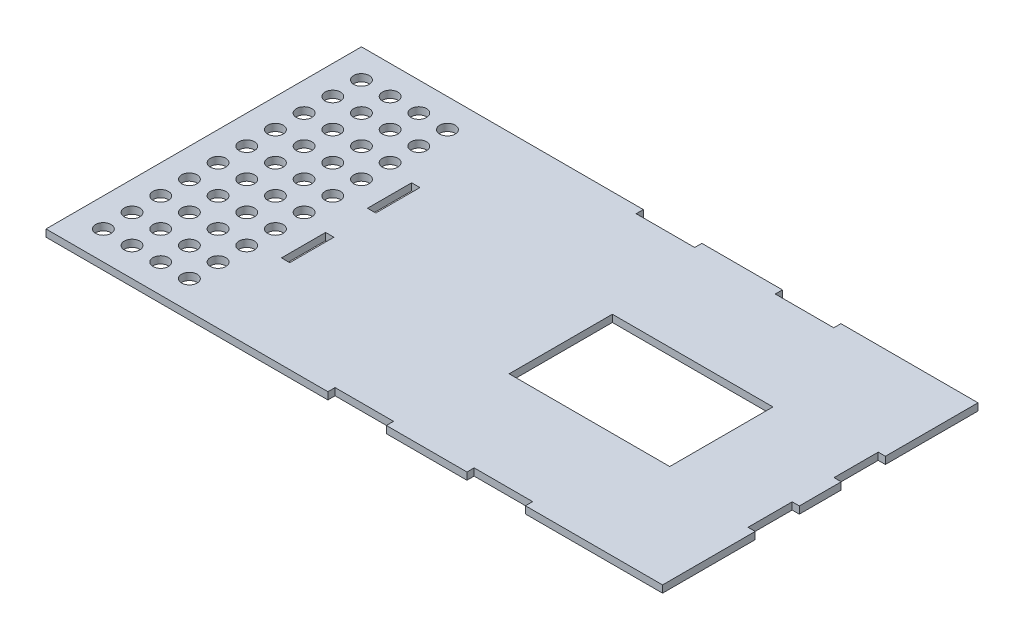
SolidWorks part; units mm, degrees
ref_plane "Front Plane" through (0, 0, 0) normal (0, 0, 1) x (1, 0, 0)
ref_plane "Top Plane" through (0, 0, 0) normal (0, 1, 0) x (1, 0, 0)
ref_plane "Right Plane" through (0, 0, 0) normal (1, 0, 0) x (0, 0, -1)
sketch "Sketch1" plane through (0, 0, 0) normal (0, 1, 0) x (1, 0, 0)
  line L1 (-101.6, -66.675) -> (101.6, -66.675)
  line L2 (-101.6, -66.675) -> (-101.6, 66.675)
  line L3 (-101.6, 66.675) -> (101.6, 66.675)
  line L4 (101.6, -66.675) -> (101.6, 66.675)
  line L5 (-101.6, -66.675) -> (101.6, 66.675) construction
  line L6 (-101.6, 66.675) -> (101.6, -66.675) construction
  point P0 (0, 0)
  dimension "D1" = 203.2
  dimension "D2" = 133.35
extrude "Boss-Extrude1" add sketch "Sketch1" along normal blind 3.175
sketch "Sketch3" plane through (0, 3.175, 0) normal (0, 1, 0) x (1, 0, 0)
  line L0 (101.6, 66.675) -> (-101.6, 66.675) construction
  line L1 (-79.121, 66.675) -> (-43.434, 66.675)
  line L2 (-79.121, 66.675) -> (-79.121, 69.85)
  line L3 (-79.121, 69.85) -> (-43.434, 69.85)
  line L4 (-43.434, 66.675) -> (-43.434, 69.85)
  line L5 (-101.6, 66.675) -> (-101.6, -66.675) construction
  line L6 (-17.526, 66.675) -> (18.161, 66.675)
  line L7 (18.161, 66.675) -> (18.161, 69.85)
  line L8 (-17.526, 69.85) -> (18.161, 69.85)
  line L9 (-17.526, 66.675) -> (-17.526, 69.85)
  line L10 (44.069, 66.675) -> (79.756, 66.675)
  line L11 (79.756, 66.675) -> (79.756, 69.85)
  line L12 (44.069, 69.85) -> (79.756, 69.85)
  line L13 (44.069, 66.675) -> (44.069, 69.85)
  line L14 (0, 0) -> (101.6, 0) construction
  line L15 (101.6, -66.675) -> (101.6, 66.675) construction
  line L16 (44.069, -66.675) -> (44.069, -69.85)
  line L17 (44.069, -69.85) -> (79.756, -69.85)
  line L18 (79.756, -66.675) -> (79.756, -69.85)
  line L19 (44.069, -66.675) -> (79.756, -66.675)
  line L20 (-17.526, -66.675) -> (-17.526, -69.85)
  line L21 (-17.526, -69.85) -> (18.161, -69.85)
  line L22 (18.161, -66.675) -> (18.161, -69.85)
  line L23 (-17.526, -66.675) -> (18.161, -66.675)
  line L24 (-43.434, -66.675) -> (-43.434, -69.85)
  line L25 (-79.121, -69.85) -> (-43.434, -69.85)
  line L26 (-79.121, -66.675) -> (-79.121, -69.85)
  line L27 (-79.121, -66.675) -> (-43.434, -66.675)
  point P6 (-61.2775, 66.675)
  dimension "D1" = 3.175
  dimension "D2" = 40.3225
  dimension "D3" = 22.479
  dimension "D4" = 35.687
  dimension "D5" = 3
extrude "Boss-Extrude2" add sketch "Sketch3" against normal blind 3.175
sketch "Sketch4" plane through (0, 3.175, 0) normal (0, 1, 0) x (1, 0, 0)
  line L0 (-101.6, 66.675) -> (-101.6, -66.675) construction
  line L1 (-101.6, 47.371) -> (-104.775, 47.371)
  line L2 (-101.6, 47.371) -> (-101.6, 28.829)
  line L3 (-101.6, 28.829) -> (-104.775, 28.829)
  line L4 (-104.775, 47.371) -> (-104.775, 28.829)
  line L5 (-104.775, 9.271) -> (-104.775, -9.271)
  line L6 (-79.121, 66.675) -> (-101.6, 66.675) construction
  line L7 (-101.6, -9.271) -> (-104.775, -9.271)
  line L8 (-101.6, 9.271) -> (-101.6, -9.271)
  line L9 (-101.6, 9.271) -> (-104.775, 9.271)
  line L10 (-104.775, -28.829) -> (-104.775, -47.371)
  line L11 (-101.6, -47.371) -> (-104.775, -47.371)
  line L12 (-101.6, -28.829) -> (-101.6, -47.371)
  line L13 (-101.6, -28.829) -> (-104.775, -28.829)
  line L14 (0, 0) -> (0, 30.8846) construction
  line L15 (101.6, -28.829) -> (104.775, -28.829)
  line L16 (101.6, -28.829) -> (101.6, -47.371)
  line L17 (101.6, -47.371) -> (104.775, -47.371)
  line L18 (104.775, -28.829) -> (104.775, -47.371)
  line L19 (101.6, 9.271) -> (104.775, 9.271)
  line L20 (101.6, 9.271) -> (101.6, -9.271)
  line L21 (101.6, -9.271) -> (104.775, -9.271)
  line L22 (104.775, 9.271) -> (104.775, -9.271)
  line L23 (104.775, 47.371) -> (104.775, 28.829)
  line L24 (101.6, 28.829) -> (104.775, 28.829)
  line L25 (101.6, 47.371) -> (101.6, 28.829)
  line L26 (101.6, 47.371) -> (104.775, 47.371)
  point P9 (-101.6, 38.1)
  point P10 (-103.1875, 47.371)
  dimension "D1" = 3.175
  dimension "D2" = 28.575
  dimension "D3" = 18.542
  dimension "D4" = 19.304
  dimension "D6" = 38.1
  dimension "D5" = 3
extrude "Boss-Extrude3" add sketch "Sketch4" against normal blind 3.175
sketch "Sketch5" plane through (0, 3.175, 0) normal (0, 1, 0) x (1, 0, 0)
  line L0 (-104.775, -28.829) -> (-104.775, -47.371) construction
  line L1 (-104.775, 69.85) -> (-168.275, 69.85)
  line L2 (-104.775, 69.85) -> (-104.775, -69.85)
  line L3 (-104.775, -69.85) -> (-168.275, -69.85)
  line L4 (-168.275, 69.85) -> (-168.275, -69.85)
  line L5 (-79.121, -69.85) -> (-43.434, -69.85) construction
  line L6 (-43.434, 69.85) -> (-79.121, 69.85) construction
  circle A0 centre (-117.475, 57.15) radius 3.429
  circle A1 centre (-130.175, 57.15) radius 3.429
  circle A2 centre (-142.875, 57.15) radius 3.429
  circle A3 centre (-155.575, 57.15) radius 3.429
  circle A4 centre (-130.175, 44.45) radius 3.429
  circle A5 centre (-142.875, 44.45) radius 3.429
  circle A6 centre (-155.575, 44.45) radius 3.429
  circle A7 centre (-130.175, 31.75) radius 3.429
  circle A8 centre (-142.875, 31.75) radius 3.429
  circle A9 centre (-155.575, 31.75) radius 3.429
  circle A10 centre (-130.175, 19.05) radius 3.429
  circle A11 centre (-142.875, 19.05) radius 3.429
  circle A12 centre (-155.575, 19.05) radius 3.429
  circle A13 centre (-130.175, 6.35) radius 3.429
  circle A14 centre (-142.875, 6.35) radius 3.429
  circle A15 centre (-155.575, 6.35) radius 3.429
  circle A16 centre (-130.175, -6.35) radius 3.429
  circle A17 centre (-142.875, -6.35) radius 3.429
  circle A18 centre (-155.575, -6.35) radius 3.429
  circle A19 centre (-130.175, -19.05) radius 3.429
  circle A20 centre (-142.875, -19.05) radius 3.429
  circle A21 centre (-155.575, -19.05) radius 3.429
  circle A22 centre (-130.175, -31.75) radius 3.429
  circle A23 centre (-142.875, -31.75) radius 3.429
  circle A24 centre (-155.575, -31.75) radius 3.429
  circle A25 centre (-130.175, -44.45) radius 3.429
  circle A26 centre (-142.875, -44.45) radius 3.429
  circle A27 centre (-155.575, -44.45) radius 3.429
  circle A28 centre (-130.175, -57.15) radius 3.429
  circle A29 centre (-142.875, -57.15) radius 3.429
  circle A30 centre (-155.575, -57.15) radius 3.429
  circle A31 centre (-117.475, 44.45) radius 3.429
  circle A32 centre (-117.475, 31.75) radius 3.429
  circle A33 centre (-117.475, 19.05) radius 3.429
  circle A34 centre (-117.475, 6.35) radius 3.429
  circle A35 centre (-117.475, -6.35) radius 3.429
  circle A36 centre (-117.475, -19.05) radius 3.429
  circle A37 centre (-117.475, -31.75) radius 3.429
  circle A38 centre (-117.475, -44.45) radius 3.429
  circle A39 centre (-117.475, -57.15) radius 3.429
  dimension "D1" = 6.858
  dimension "D6" = 63.5
  dimension "D2" = 12.7
  dimension "D3" = 12.7
  dimension "D4" = 4
  dimension "D5" = 10
extrude "Boss-Extrude4" add sketch "Sketch5" against normal blind 3.175
sketch "Sketch6" plane through (0, 3.175, 0) normal (0, 1, 0) x (1, 0, 0)
  line L6 (0, 0) -> (0, -69.8507) construction
  line L8 (0, 0) -> (104.775, 0) construction
  line L18 (-79.121, 66.675) -> (-79.121, 69.85)
  line L19 (-104.775, 69.85) -> (-79.121, 69.85)
  line L20 (-104.775, 58.6105) -> (-104.775, 69.85)
  line L21 (-101.6, 66.675) -> (-79.121, 66.675)
  line L22 (-104.775, 47.371) -> (-104.775, 69.85) construction
  line L23 (-101.6, 47.371) -> (-104.775, 47.371)
  line L24 (-101.6, 47.371) -> (-101.6, 66.675)
  line L26 (-104.775, 47.371) -> (-104.775, 58.6105)
  line L27 (-104.775, -47.371) -> (-104.775, -58.6105)
  line L28 (-101.6, -47.371) -> (-101.6, -66.675)
  line L29 (-101.6, -47.371) -> (-104.775, -47.371)
  line L30 (-101.6, -66.675) -> (-79.121, -66.675)
  line L31 (-104.775, -58.6105) -> (-104.775, -69.85)
  line L32 (-104.775, -69.85) -> (-79.121, -69.85)
  line L33 (-79.121, -66.675) -> (-79.121, -69.85)
  line L34 (79.121, -66.675) -> (79.121, -69.85)
  line L35 (104.775, -69.85) -> (79.121, -69.85)
  line L36 (104.775, -58.6105) -> (104.775, -69.85)
  line L37 (101.6, -66.675) -> (79.121, -66.675)
  line L38 (101.6, -47.371) -> (104.775, -47.371)
  line L39 (101.6, -47.371) -> (101.6, -66.675)
  line L40 (104.775, -47.371) -> (104.775, -58.6105)
  line L41 (104.775, 47.371) -> (104.775, 58.6105)
  line L42 (101.6, 47.371) -> (101.6, 66.675)
  line L43 (101.6, 47.371) -> (104.775, 47.371)
  line L44 (101.6, 66.675) -> (79.121, 66.675)
  line L45 (104.775, 58.6105) -> (104.775, 69.85)
  line L46 (104.775, 69.85) -> (79.121, 69.85)
  line L47 (79.121, 66.675) -> (79.121, 69.85)
extrude "Boss-Extrude5" add sketch "Sketch6" against normal blind 3.175
sketch "Sketch7" plane through (0, 3.175, 0) normal (0, 1, 0) x (1, 0, 0)
  line L0 (-101.6, -28.829) -> (-104.775, -28.829) construction
  line L1 (-101.346, 28.829) -> (-105.029, 28.829)
  line L2 (-101.346, 28.829) -> (-101.346, 9.271)
  line L3 (-101.346, 9.271) -> (-105.029, 9.271)
  line L4 (-105.029, 28.829) -> (-105.029, 9.271)
  line L5 (-105.029, -9.271) -> (-101.346, -9.271)
  line L6 (-105.029, -9.271) -> (-105.029, -28.829)
  line L7 (-105.029, -28.829) -> (-101.346, -28.829)
  line L8 (-101.346, -9.271) -> (-101.346, -28.829)
  line L9 (-104.775, -9.271) -> (-101.6, -9.271) construction
  line L10 (-101.6, 9.271) -> (-104.775, 9.271) construction
  line L11 (-104.775, 28.829) -> (-101.6, 28.829) construction
  point P16 (-103.1875, 28.829)
  dimension "D1" = 3.683
extrude "Cut-Extrude1" cut sketch "Sketch7" against normal through all
sketch "Sketch8" plane through (0, 0, 0) normal (0, 1, 0) x (1, 0, 0)
  line L0 (101.6, 9.271) -> (101.6, 28.829) construction
  line L1 (60.96, 22.86) -> (-10.16, 22.86)
  line L2 (60.96, 22.86) -> (60.96, -22.86)
  line L3 (60.96, -22.86) -> (-10.16, -22.86)
  line L4 (-10.16, 22.86) -> (-10.16, -22.86)
  line L5 (60.96, 22.86) -> (-10.16, -22.86) construction
  line L6 (60.96, -22.86) -> (-10.16, 22.86) construction
  point P0 (25.4, 0)
  dimension "D1" = 45.72
  dimension "D2" = 71.12
  dimension "D3" = 76.2
extrude "Cut-Extrude4" cut sketch "Sketch8" along normal through all
